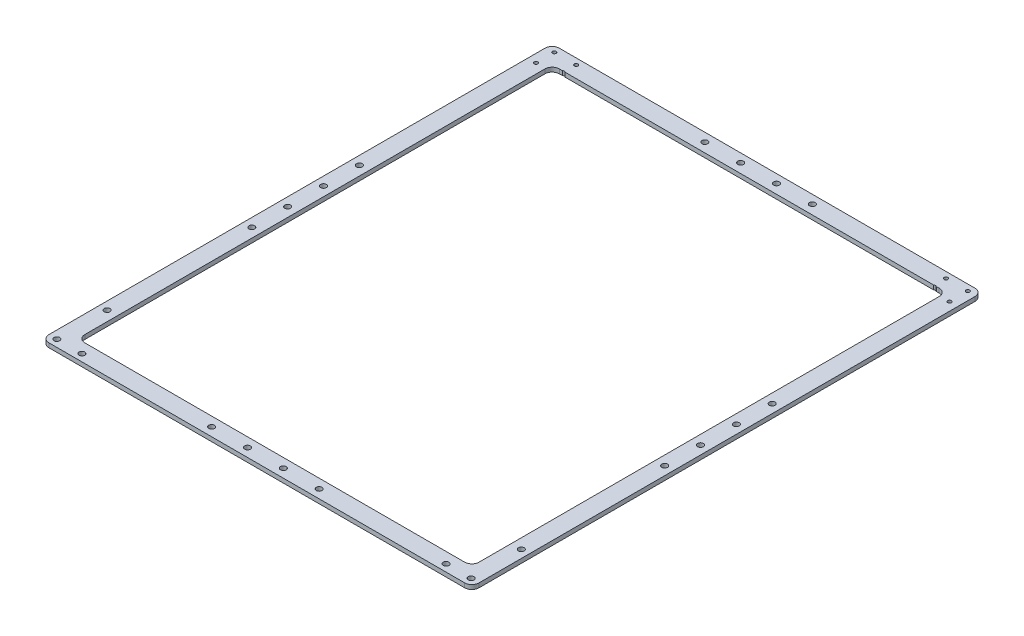
SolidWorks part; units mm, degrees
ref_plane "Front Plane" through (0, 0, 0) normal (0, 0, 1) x (1, 0, 0)
ref_plane "Top Plane" through (0, 0, 0) normal (0, 1, 0) x (1, 0, 0)
ref_plane "Right Plane" through (0, 0, 0) normal (1, 0, 0) x (0, 0, -1)
sketch "Sketch1" plane through (0, 0, 0) normal (0, 1, 0) x (1, 0, 0)
  line L0 (0, 0) -> (0, 645.6687) construction
  line L1 (-300, -365) -> (300, -365)
  line L2 (-300, -365) -> (-300, 365)
  line L3 (-300, 365) -> (300, 365)
  line L4 (300, -365) -> (300, 365)
  line L5 (-300, -365) -> (300, 365) construction
  line L6 (-300, 365) -> (300, -365) construction
  line L11 (-300, -300) -> (300, 300) construction
  line L12 (-300, 300) -> (300, -300) construction
  point P0 (0, 0)
  point P6 (0, 0)
  dimension "D1" = 730
  dimension "D2" = 600
extrude "Boss-Extrude1" add sketch "Sketch1" along normal blind 6
sketch "Sketch2" plane through (0, 6, 0) normal (0, 1, 0) x (1, 0, 0)
  line L0 (-300, 365) -> (-300, -365) construction
  line L1 (-265, 330) -> (-253, 330)
  line L2 (-265, 330) -> (-265, -290)
  line L3 (-265, -290) -> (-253, -290)
  line L4 (-253, 330) -> (-253, -290)
  line L5 (-259, 330) -> (-259, 320)
  circle A0 centre (-259, 320) radius 2.75
  dimension "D6" = 5.5
  dimension "D1" = 35
  dimension "D2" = 12
  dimension "D3" = 290
  dimension "D4" = 620
  dimension "D5" = 10
extrude "Cut-Extrude1" cut sketch "Sketch2" against normal through all
pattern_linear "LPattern1" count 25 spacing 25 along (0, 0, 1) of "Cut-Extrude1"
mirror "Mirror2" about plane through (0, 0, 0) normal (1, 0, 0) of "LPattern1", "Cut-Extrude1"
sketch "Sketch3" plane through (0, 6, 0) normal (0, 1, 0) x (1, 0, 0)
  line L0 (-300, 365) -> (-300, -365) construction
  line L1 (-289, -355) -> (-254, -355) construction
  line L2 (-289, -355) -> (-289, -285) construction
  line L3 (-289, -285) -> (-254, -285) construction
  line L4 (-254, -355) -> (-254, -285) construction
  line L5 (-300, -365) -> (300, -365) construction
  circle A0 centre (-289, -285) radius 4
  circle A2 centre (-254, -355) radius 4
  circle A3 centre (-289, -355) radius 4
  circle A4 centre (-236.98, -302.5) radius 4
  dimension "D5" = 8
  dimension "D1" = 35
  dimension "D2" = 70
  dimension "D3" = 11
  dimension "D4" = 10
  dimension "D7" = 17.5
  dimension "D8" = 52.02
extrude "Cut-Extrude2" cut sketch "Sketch3" against normal blind 13
mirror "Mirror3" about plane through (0, 0, 0) normal (1, 0, 0) of "Cut-Extrude2"
sketch "Sketch5" plane through (0, 6, 0) normal (0, 1, 0) x (1, 0, 0)
  line L0 (-265, 330) -> (-253, 330) construction
  line L1 (-280.98, 306) -> (-295.98, 306)
  line L2 (-280.98, 306) -> (-280.98, 346)
  line L3 (-280.98, 346) -> (-295.98, 346)
  line L4 (-295.98, 306) -> (-295.98, 346)
  line L5 (-280.98, 346) -> (-250.98, 346)
  line L6 (-280.98, 346) -> (-280.98, 331)
  line L7 (-280.98, 331) -> (-250.98, 331)
  line L8 (-250.98, 346) -> (-250.98, 331)
  line L10 (-250.98, 338.5) -> (-354.0628, 338.5) construction
  line L11 (-288.48, 306) -> (-288.48, 373.0529) construction
  line L12 (-259, 320) -> (-259, 373.0529) construction
  circle A0 centre (-288.48, 313) radius 2.55
  circle A1 centre (-257.98, 338.5) radius 2.55
  circle A2 centre (-288.48, 338.5) radius 2.55
  dimension "D7" = 5.1
  dimension "D8" = 5.1
  dimension "D11" = 0
  dimension "D13" = 5.1
  dimension "D1" = 15
  dimension "D2" = 15
  dimension "D3" = 1
  dimension "D4" = 30
  dimension "D5" = 40
  dimension "D6" = 29.48
  dimension "D9" = 7
  dimension "D10" = 7
  dimension "D12" = 0
extrude "Cut-Extrude4" cut sketch "Sketch5" against normal through all contours A0 | A1 | A2
mirror "Mirror5" about plane through (0, 0, 0) normal (1, 0, 0) of "Cut-Extrude4"
sketch "Sketch6" plane through (0, 6, 0) normal (0, 1, 0) x (1, 0, 0)
  line L0 (300, -365) -> (300, 365) construction
  line L1 (-300, 365) -> (300, 365)
  line L2 (-300, 365) -> (-300, 347)
  line L3 (-300, 347) -> (300, 347)
  line L4 (300, 365) -> (300, 347)
  dimension "D1" = 18
extrude "Cut-Extrude5" cut sketch "Sketch6" against normal up to surface (6 mm away) contours L4 L1 L2 L3 up to face at (288.48, 0, -310.45)
sketch "Sketch7" plane through (0, 6, 0) normal (0, 1, 0) x (1, 0, 0)
  line L0 (-300, 347) -> (300, 347) construction
  line L1 (-300, -9) -> (300, -9) construction
  line L2 (-300, 347) -> (-300, -365) construction
  line L3 (300, -365) -> (300, 347) construction
  line L4 (0, 347) -> (0, -9) construction
  circle A0 centre (-75, 335) radius 4
  circle A1 centre (-25, 335) radius 4
  circle A2 centre (25, 335) radius 4
  circle A3 centre (75, 335) radius 4
  circle A4 centre (75, -353) radius 4
  circle A5 centre (25, -353) radius 4
  circle A6 centre (-25, -353) radius 4
  circle A7 centre (-75, -353) radius 4
  dimension "D1" = 8
  dimension "D2" = 50
  dimension "D3" = 50
  dimension "D4" = 50
  dimension "D5" = 12
  dimension "D6" = 25
extrude "Cut-Extrude6" cut sketch "Sketch7" against normal up to next
sketch "Sketch8" plane through (0, 6, 0) normal (0, 1, 0) x (1, 0, 0)
  line L0 (-300, -9) -> (300, -9) construction
  line L1 (-300, 347) -> (-300, -365) construction
  line L2 (300, -365) -> (300, 347) construction
  line L3 (0, -365) -> (0, 347) construction
  line L4 (-300, -365) -> (300, -365) construction
  line L5 (-300, 347) -> (300, 347) construction
  circle A0 centre (288, 66) radius 4
  circle A4 centre (288, 16) radius 4
  circle A5 centre (288, -34) radius 4
  circle A6 centre (288, -84) radius 4
  dimension "D1" = 75
  dimension "D3" = 8
  dimension "D2" = 4
  dimension "D6" = 12
extrude "Cut-Extrude7" cut sketch "Sketch8" against normal up to next
mirror "Mirror6" about plane through (0, 0, 0) normal (1, 0, 0) of "Cut-Extrude7"
sketch "Sketch9" plane through (0, 6, 0) normal (0, 1, 0) x (1, 0, 0)
  line L0 (0, 347) -> (0, -365) construction
  line L1 (-300, 347) -> (300, 347) construction
  line L2 (-300, -365) -> (300, -365) construction
  line L3 (300, -9) -> (-300, -9) construction
  line L4 (300, -365) -> (300, 347) construction
  line L5 (-300, 347) -> (-300, -365) construction
  line L7 (-275, -340) -> (275, -340)
  line L8 (-275, -340) -> (-275, 322)
  line L9 (-275, 322) -> (275, 322)
  line L10 (275, -340) -> (275, 322)
  line L11 (-275, -340) -> (275, 322) construction
  line L12 (-275, 322) -> (275, -340) construction
  point P12 (0, -9)
  dimension "D1" = 25
  dimension "D2" = 25
extrude "Cut-Extrude8" cut sketch "Sketch9" against normal up to next
fillet "Fillet2" radius 10 8 edges at (300, 3, -347) (300, 3, 365) (-300, 3, 365) (-300, 3, -347) (-275, 3, -322) (275, 3, -322) (275, 3, 340) (-275, 3, 340)
